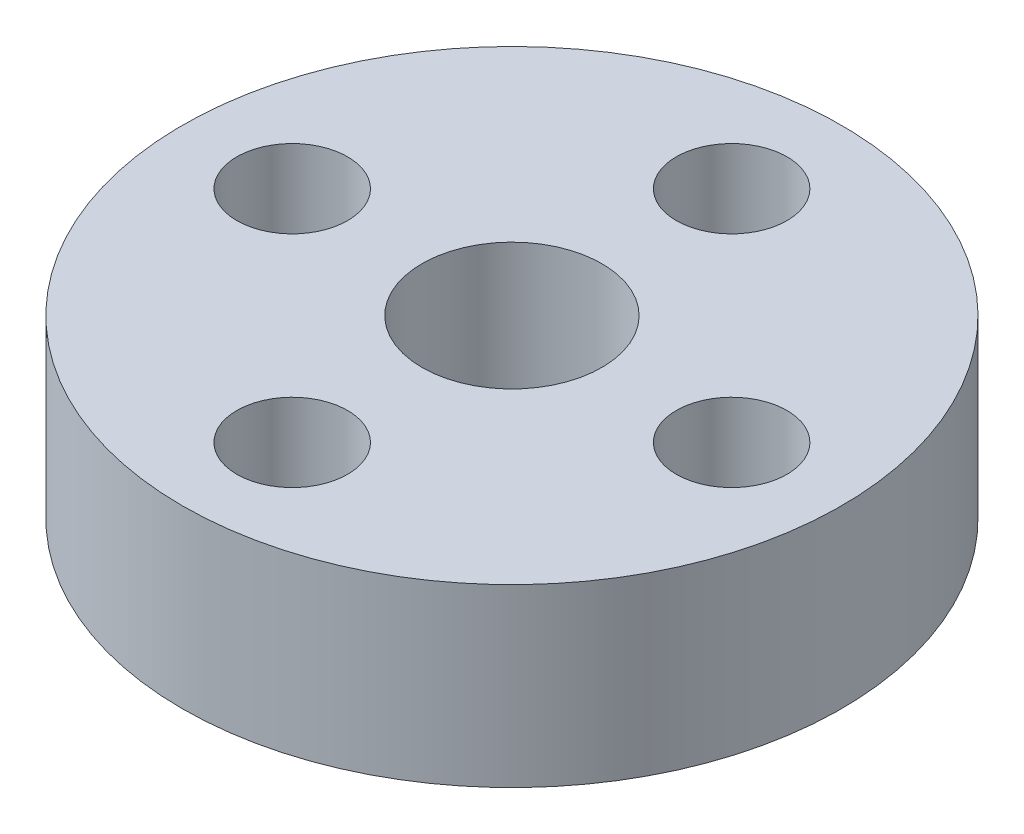
SolidWorks part; units mm, degrees
ref_plane "Front Plane" through (0, 0, 0) normal (0, 0, 1) x (1, 0, 0)
ref_plane "Top Plane" through (0, 0, 0) normal (0, 1, 0) x (1, 0, 0)
ref_plane "Right Plane" through (0, 0, 0) normal (1, 0, 0) x (0, 0, -1)
sketch "Sketch1" plane through (0, 0, 0) normal (0, 1, 0) x (1, 0, 0)
  circle A0 centre (0, 0) radius 9.525
  circle A1 centre (0, 6.35) radius 1.6
  circle A2 centre (6.35, 0) radius 1.6
  circle A3 centre (0, -6.35) radius 1.6
  circle A4 centre (-6.35, 0) radius 1.6
  circle A5 centre (0, 0) radius 2.6
  point P15 (0, 0)
  dimension "D1" = 19.05
  dimension "D2" = 3.2
  dimension "D3" = 6.35
  dimension "D4" = 4
  dimension "D6" = 5.2
extrude "Boss-Extrude1" add sketch "Sketch1" along normal blind 5.08
